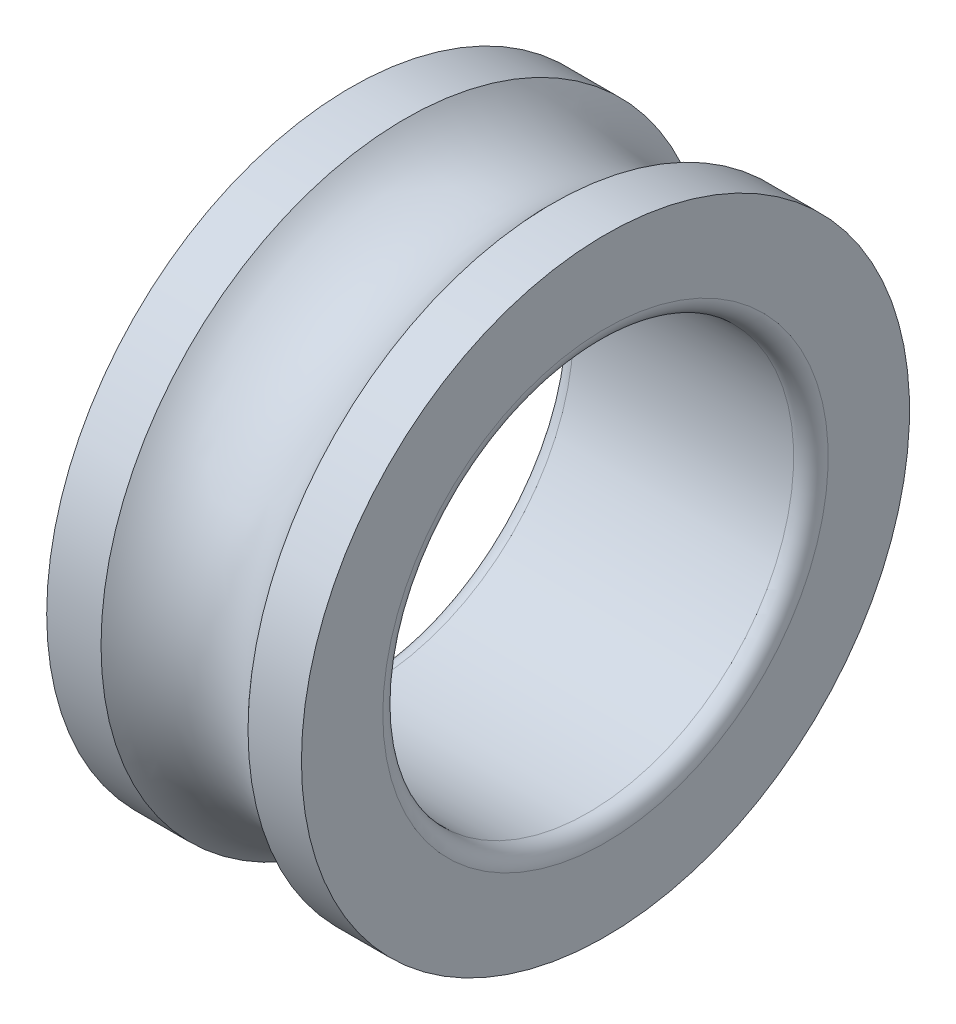
SolidWorks part; units mm, degrees
ref_plane "Front Plane" through (0, 0, 0) normal (0, 0, 1) x (1, 0, 0)
ref_plane "Top Plane" through (0, 0, 0) normal (0, 1, 0) x (1, 0, 0)
ref_plane "Right Plane" through (0, 0, 0) normal (1, 0, 0) x (0, 0, -1)
sketch "Sketch1" plane through (0, 0, 0) normal (0, 0, 1) x (1, 0, 0)
  line L0 (-17.7215, 0) -> (42.9658, 0) construction
  line L1 (0, 25) -> (0, 0) construction
  line L6 (-15.5, 37) -> (-8.8885, 37)
  line L7 (-15.5, 37) -> (-15.5, 27.1)
  line L8 (-13.4, 25) -> (13.4, 25)
  line L9 (15.5, 37) -> (15.5, 27.1)
  line L10 (-15.5, 37) -> (15.5, 25) construction
  line L11 (-15.5, 25) -> (15.5, 37) construction
  line L12 (9, 37) -> (15.5, 37)
  arc A0 (9, 37) -> (-8.8885, 37) centre (0.0557, 45) cw
  arc A1 (13.4, 25) -> (15.5, 27.1) centre (13.4, 27.1) ccw
  arc A2 (-15.5, 27.1) -> (-13.4, 25) centre (-13.4, 27.1) ccw
  point P3 (0, 31)
  dimension "D5" = 12
  dimension "D7" = 2.1
  dimension "D1" = 37
  dimension "D2" = 25
  dimension "D3" = 8
  dimension "D4" = 31
  dimension "D6" = 6.5
revolve "Revolve1" add sketch "Sketch1" angle 360 about L0
